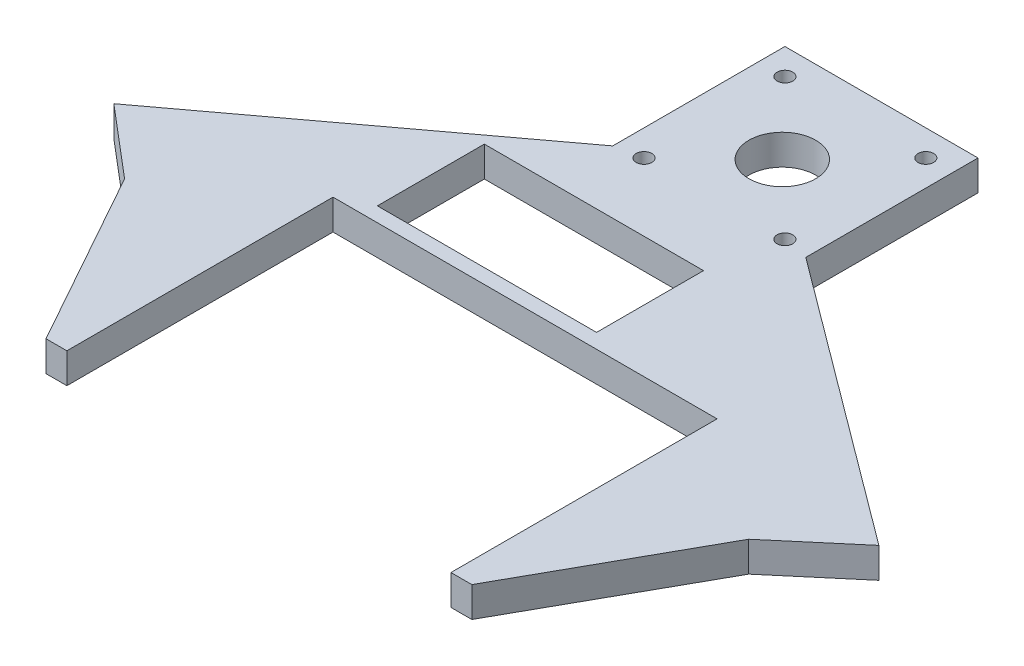
SolidWorks part; units mm, degrees
ref_plane "Plan de face" through (0, 0, 0) normal (0, 0, 1) x (1, 0, 0)
ref_plane "Plan de dessus" through (0, 0, 0) normal (0, 1, 0) x (1, 0, 0)
ref_plane "Plan de droite" through (0, 0, 0) normal (1, 0, 0) x (0, 0, -1)
sketch "Esquisse1" plane through (0, 0, 0) normal (0, 1, 0) x (1, 0, 0)
  line L13 (0, 0) -> (-18.5, 0)
  line L14 (-18.5, 0) -> (-18.5, -33)
  line L15 (-18.5, -33) -> (-73.3, -73.794)
  line L23 (-59.8, -85.2412) -> (-40.8, -119.3)
  line L25 (-36.8, -68.3) -> (0, -68.3)
  line L26 (0, -68.3) -> (0, 0)
  line L27 (-40.8, -119.3) -> (-36.8, -119.3)
  line L28 (-36.8, -119.3) -> (-36.8, -68.3)
  line L30 (-73.3, -73.794) -> (-59.8, -85.2412)
  point P2 (-60.4538, -93.0292)
  point P3 (-53.5773, -138.3825)
  point P5 (-73.3, -89.8118)
  point P6 (-177.8354, -39.6723)
  point P12 (-61.1857, -140.2482)
  point P14 (-65.6515, -99.6315)
  point P15 (-187.9039, -46.0419)
  point P16 (-69.066, -105.2836)
  point P17 (-73.3, -113.9973)
  dimension "D1" = 18.5
  dimension "D2" = 73.3
  dimension "D3" = 68.3
  dimension "D4" = 36.8
  dimension "D5" = 4
  dimension "D6" = 39
  dimension "D7" = 23
  dimension "D8" = 17.7
  dimension "D9" = 51
  dimension "D10" = 33
extrude "Boss.-Extru.1" add sketch "Esquisse1" along normal blind 5.8
sketch "Esquisse2" plane through (0, 5.8, 0) normal (0, 1, 0) x (1, 0, 0)
  line L1 (0, 0) -> (-18.5, 0) construction
  line L3 (-18.5, 0) -> (-18.5, -33) construction
  line L4 (0, -68.3) -> (0, 0) construction
  circle A0 centre (-13.5, -5) radius 1.5
  circle A1 centre (0, -19) radius 6.4
  circle A2 centre (-13.5, -32) radius 1.5
  point P4 (0, 0)
  dimension "D2" = 3
  dimension "D3" = 12.8
  dimension "D6" = 3
  dimension "D1" = 13.5
  dimension "D4" = 19
  dimension "D5" = 5
  dimension "D7" = 27
  dimension "D8" = 5
extrude "Enlèv. mat.-Extru.1" cut sketch "Esquisse2" against normal up to surface (5.8 mm away) up to face at (-31.6111, 0, 63.0261)
mirror "Symétrie2" about plane through (0, 5.8, 68.3) normal (-1, 0, 0) of "Enlèv. mat.-Extru.1", "Boss.-Extru.1"
sketch "Esquisse3" plane through (0, 5.8, 0) normal (0, 1, 0) x (1, 0, 0)
  line L0 (18.5, 0) -> (-18.5, 0) construction
  line L1 (-31.1, -45) -> (10.9, -45)
  line L2 (-31.1, -45) -> (-31.1, -65.5)
  line L3 (-31.1, -65.5) -> (10.9, -65.5)
  line L4 (10.9, -45) -> (10.9, -65.5)
  line L6 (-36.8, -119.3) -> (-36.8, -68.3) construction
  dimension "D1" = 45
  dimension "D2" = 20.5
  dimension "D3" = 42
  dimension "D4" = 5.7
extrude "Enlèv. mat.-Extru.2" cut sketch "Esquisse3" against normal up to surface (5.8 mm away) up to face at (13.5, 0, 6.5)
